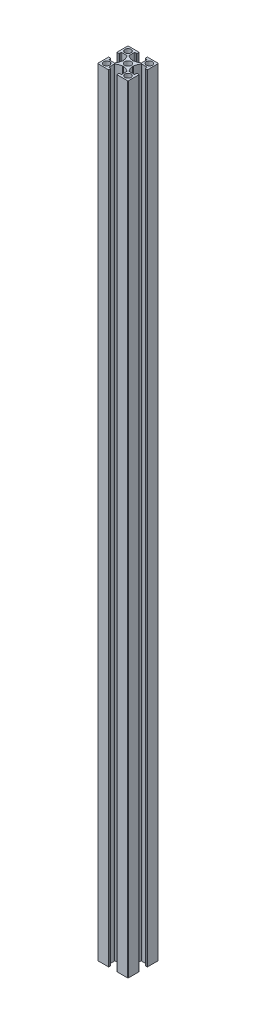
SolidWorks part; units mm, degrees
ref_plane "정면도" through (0, 0, 0) normal (0, 0, 1) x (1, 0, 0)
ref_plane "평면도" through (0, 0, 0) normal (0, 1, 0) x (1, 0, 0)
ref_plane "우측면도" through (0, 0, 0) normal (1, 0, 0) x (0, 0, -1)
sketch "스케치1" plane through (0, 0, 0) normal (0, 1, 0) x (1, 0, 0)
  line B0 (4.15, 4.9427) -> (4.15, 8.2)
  line B1 (3.85, 8.5) -> (2.95, 8.5)
  line B2 (2.65, 8.8) -> (2.65, 9.7)
  line B3 (2.95, 10) -> (9.7, 10)
  line B4 (10, 9.7) -> (10, 2.95)
  line B5 (9.7, 2.65) -> (8.8, 2.65)
  line B6 (8.5, 2.95) -> (8.5, 3.85)
  line B7 (8.2, 4.15) -> (4.9427, 4.15)
  line B8 (3.3073, 0.3073) -> (3, 0)
  line B9 (3, 0) -> (3.3073, -0.3073)
  line B10 (4.9427, -4.15) -> (8.2, -4.15)
  line B11 (8.5, -3.85) -> (8.5, -2.95)
  line B12 (8.8, -2.65) -> (9.7, -2.65)
  line B13 (10, -2.95) -> (10, -9.7)
  line B14 (9.7, -10) -> (2.95, -10)
  line B15 (2.65, -9.7) -> (2.65, -8.8)
  line B16 (2.95, -8.5) -> (3.85, -8.5)
  line B17 (4.15, -8.2) -> (4.15, -4.9427)
  line B18 (0.3073, -3.3073) -> (0, -3)
  line B19 (0, -3) -> (-0.3073, -3.3073)
  line B20 (-4.15, -4.9427) -> (-4.15, -8.2)
  line B21 (-3.85, -8.5) -> (-2.95, -8.5)
  line B22 (-2.65, -8.8) -> (-2.65, -9.7)
  line B23 (-2.95, -10) -> (-9.7, -10)
  line B24 (-10, -9.7) -> (-10, -2.95)
  line B25 (-9.7, -2.65) -> (-8.8, -2.65)
  line B26 (-8.5, -2.95) -> (-8.5, -3.85)
  line B27 (-8.2, -4.15) -> (-4.9427, -4.15)
  line B28 (-3.3073, -0.3073) -> (-3, 0)
  line B29 (-3, 0) -> (-3.3073, 0.3073)
  line B30 (-4.9427, 4.15) -> (-8.2, 4.15)
  line B31 (-8.5, 3.85) -> (-8.5, 2.95)
  line B32 (-8.8, 2.65) -> (-9.7, 2.65)
  line B33 (-10, 2.95) -> (-10, 9.7)
  line B34 (-9.7, 10) -> (-2.95, 10)
  line B35 (-2.65, 9.7) -> (-2.65, 8.8)
  line B36 (-2.95, 8.5) -> (-3.85, 8.5)
  line B37 (-4.15, 8.2) -> (-4.15, 4.9427)
  line B38 (-0.3073, 3.3073) -> (0, 3)
  line B39 (0, 3) -> (0.3073, 3.3073)
  line B40 (-9.5, 7) -> (-4.5, 7) construction
  line B41 (-7, 9.5) -> (-7, 4.5) construction
  line B42 (-9.5, -7) -> (-4.5, -7) construction
  line B43 (-7, -9.5) -> (-7, -4.5) construction
  line B44 (9.5, 7) -> (4.5, 7) construction
  line B45 (7, 9.5) -> (7, 4.5) construction
  line B46 (7, -9.5) -> (7, -4.5) construction
  line B47 (9.5, -7) -> (4.5, -7) construction
  circle B48 centre (0, 0) radius 2.15
  arc B49 (4.15, 8.2) -> (3.85, 8.5) centre (3.85, 8.2) ccw
  arc B50 (2.65, 8.8) -> (2.95, 8.5) centre (2.95, 8.8) ccw
  arc B51 (2.95, 10) -> (2.65, 9.7) centre (2.95, 9.7) ccw
  arc B52 (10, 9.7) -> (9.7, 10) centre (9.7, 9.7) ccw
  arc B53 (9.7, 2.65) -> (10, 2.95) centre (9.7, 2.95) ccw
  arc B54 (8.5, 2.95) -> (8.8, 2.65) centre (8.8, 2.95) ccw
  arc B55 (8.5, 3.85) -> (8.2, 4.15) centre (8.2, 3.85) ccw
  arc B56 (4.9427, 4.15) -> (4.7078, 4.0366) centre (4.9427, 3.85) ccw
  arc B57 (4.7078, 4.0366) -> (3.3073, 0.3073) centre (9.7908, 0) ccw
  arc B58 (3.3073, -0.3073) -> (4.7078, -4.0366) centre (9.7908, 0) ccw
  arc B59 (4.7078, -4.0366) -> (4.9427, -4.15) centre (4.9427, -3.85) ccw
  arc B60 (8.2, -4.15) -> (8.5, -3.85) centre (8.2, -3.85) ccw
  arc B61 (8.8, -2.65) -> (8.5, -2.95) centre (8.8, -2.95) ccw
  arc B62 (10, -2.95) -> (9.7, -2.65) centre (9.7, -2.95) ccw
  arc B63 (9.7, -10) -> (10, -9.7) centre (9.7, -9.7) ccw
  arc B64 (2.65, -9.7) -> (2.95, -10) centre (2.95, -9.7) ccw
  arc B65 (2.95, -8.5) -> (2.65, -8.8) centre (2.95, -8.8) ccw
  arc B66 (3.85, -8.5) -> (4.15, -8.2) centre (3.85, -8.2) ccw
  arc B67 (4.15, -4.9427) -> (4.0366, -4.7078) centre (3.85, -4.9427) ccw
  arc B68 (4.0366, -4.7078) -> (0.3073, -3.3073) centre (0, -9.7908) ccw
  arc B69 (-0.3073, -3.3073) -> (-4.0366, -4.7078) centre (0, -9.7908) ccw
  arc B70 (-4.0366, -4.7078) -> (-4.15, -4.9427) centre (-3.85, -4.9427) ccw
  arc B71 (-4.15, -8.2) -> (-3.85, -8.5) centre (-3.85, -8.2) ccw
  arc B72 (-2.65, -8.8) -> (-2.95, -8.5) centre (-2.95, -8.8) ccw
  arc B73 (-2.95, -10) -> (-2.65, -9.7) centre (-2.95, -9.7) ccw
  arc B74 (-10, -9.7) -> (-9.7, -10) centre (-9.7, -9.7) ccw
  arc B75 (-9.7, -2.65) -> (-10, -2.95) centre (-9.7, -2.95) ccw
  arc B76 (-8.5, -2.95) -> (-8.8, -2.65) centre (-8.8, -2.95) ccw
  arc B77 (-8.5, -3.85) -> (-8.2, -4.15) centre (-8.2, -3.85) ccw
  arc B78 (-4.9427, -4.15) -> (-4.7078, -4.0366) centre (-4.9427, -3.85) ccw
  arc B79 (-4.7078, -4.0366) -> (-3.3073, -0.3073) centre (-9.7908, 0) ccw
  arc B80 (-3.3073, 0.3073) -> (-4.7078, 4.0366) centre (-9.7908, 0) ccw
  arc B81 (-4.7078, 4.0366) -> (-4.9427, 4.15) centre (-4.9427, 3.85) ccw
  arc B82 (-8.2, 4.15) -> (-8.5, 3.85) centre (-8.2, 3.85) ccw
  arc B83 (-8.8, 2.65) -> (-8.5, 2.95) centre (-8.8, 2.95) ccw
  arc B84 (-10, 2.95) -> (-9.7, 2.65) centre (-9.7, 2.95) ccw
  arc B85 (-9.7, 10) -> (-10, 9.7) centre (-9.7, 9.7) ccw
  arc B86 (-2.65, 9.7) -> (-2.95, 10) centre (-2.95, 9.7) ccw
  arc B87 (-2.95, 8.5) -> (-2.65, 8.8) centre (-2.95, 8.8) ccw
  arc B88 (-3.85, 8.5) -> (-4.15, 8.2) centre (-3.85, 8.2) ccw
  arc B89 (-4.15, 4.9427) -> (-4.0366, 4.7078) centre (-3.85, 4.9427) ccw
  arc B90 (-4.0366, 4.7078) -> (-0.3073, 3.3073) centre (0, 9.7908) ccw
  arc B91 (0.3073, 3.3073) -> (4.0366, 4.7078) centre (0, 9.7908) ccw
  arc B92 (4.0366, 4.7078) -> (4.15, 4.9427) centre (3.85, 4.9427) ccw
  circle B93 centre (-7, 7) radius 2
  circle B94 centre (-7, -7) radius 2
  circle B95 centre (7, 7) radius 2
  circle B96 centre (7, -7) radius 2
sketch_block_instance "블록1-1"
sketch_block "블록1"
extrude "보스-돌출1" add sketch "스케치1" along normal blind 510 contours B92 B91 B39 B38 B90 B89 B37 B88 B36 B87 B35 B86 B34 B85 B33 B84 B32 B83 B31 B82 B30 B81 B80 B29 B28 B79 B78 B27 B77 B26 B76 B25 B75 B24 B74 B23 B73 B22 B72 B21 B71 B20 B70 B69 B19 B18 B68 B67 B17 B66 B16
